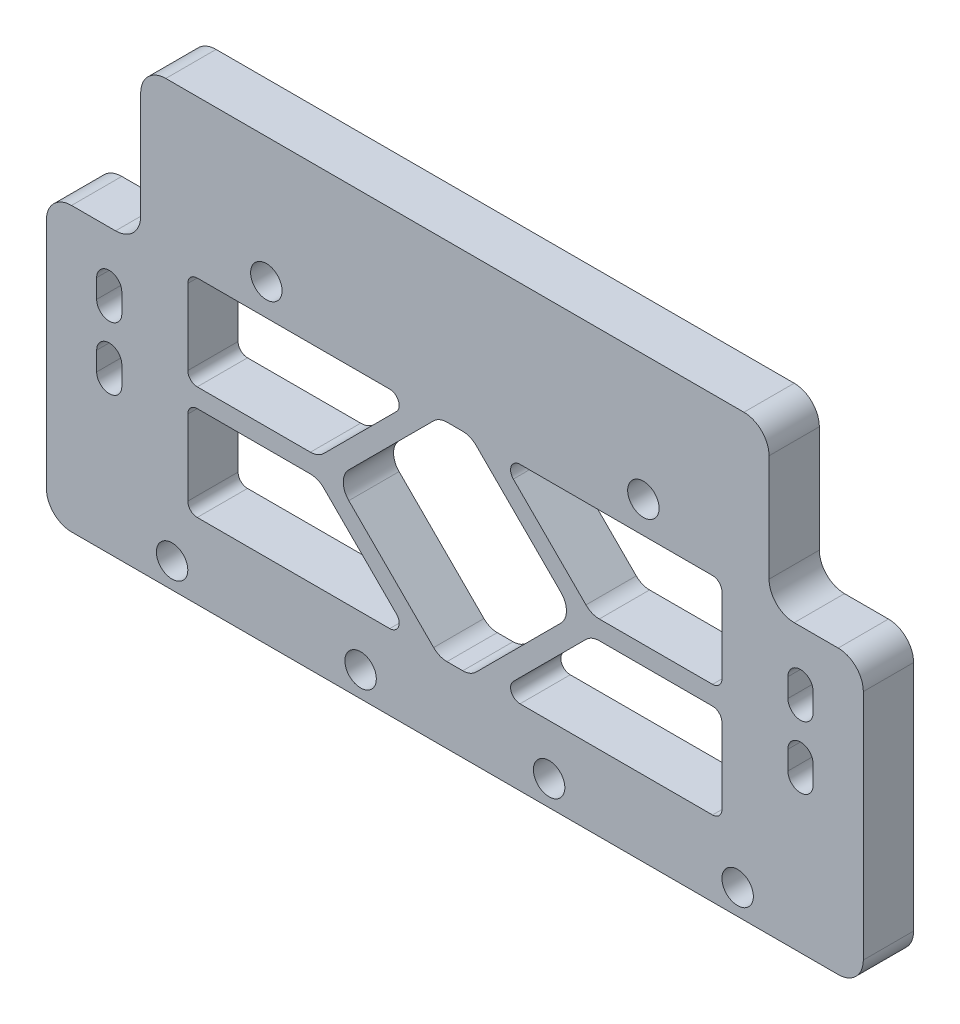
SolidWorks part; units mm, degrees
ref_plane "Plan de face" through (0, 0, 0) normal (0, 0, 1) x (1, 0, 0)
ref_plane "Plan de dessus" through (0, 0, 0) normal (0, 1, 0) x (1, 0, 0)
ref_plane "Plan de droite" through (0, 0, 0) normal (1, 0, 0) x (0, 0, -1)
sketch "Esquisse1" plane through (0, 0, 0) normal (0, 0, 1) x (1, 0, 0)
  line L1 (65, 4) -> (65, 41)
  line L2 (61, 45) -> (54, 45)
  line L3 (50, 49) -> (50, 66)
  line L4 (46, 70) -> (-46, 70)
  line L5 (0, 70) -> (0, 0) construction
  line L6 (-65, 4) -> (-65, 41)
  line L7 (-61, 45) -> (-54, 45)
  line L8 (-50, 49) -> (-50, 66)
  line L12 (-65, 0) -> (65, 0) construction
  line L13 (-61, 0) -> (61, 0)
  arc A0 (54, 45) -> (50, 49) centre (54, 49) cw
  arc A1 (61, 45) -> (65, 41) centre (61, 41) cw
  arc A2 (65, 4) -> (61, 0) centre (61, 4) cw
  arc A3 (-65, 4) -> (-61, 0) centre (-61, 4) ccw
  arc A4 (-54, 45) -> (-50, 49) centre (-54, 49) ccw
  arc A5 (-61, 45) -> (-65, 41) centre (-61, 41) ccw
  arc A6 (50, 66) -> (46, 70) centre (46, 66) ccw
  arc A7 (-46, 70) -> (-50, 66) centre (-46, 66) ccw
  point P13 (50, 45)
  point P16 (65, 45)
  point P25 (-50, 45)
  point P28 (-65, 45)
  point P31 (50, 70)
  point P34 (-50, 70)
  dimension "D5" = 4
  dimension "D1" = 65
  dimension "D2" = 15
  dimension "D3" = 45
  dimension "D4" = 25
  dimension "D7" = 130
extrude "Boss.-Extru.1" add sketch "Esquisse1" along normal blind 8
sketch "Esquisse2" plane through (0, 0, 8) normal (0, 0, 1) x (1, 0, 0)
  line L0 (65, 4) -> (65, 41) construction
  line L1 (-65, 0) -> (65, 0) construction
  line L2 (-65, 0) -> (-65, 10) construction
  line L3 (-65, 10) -> (65, 10) construction
  line L4 (65, 0) -> (65, 10) construction
  line L5 (-65, 5) -> (79.0692, 5) construction
  line L6 (0, 10) -> (0, -12.3812) construction
  line L7 (50, 49) -> (50, 66) construction
  line L8 (46, 70) -> (-46, 70) construction
  line L9 (0, 70) -> (0, 54.5793) construction
  circle A4 centre (30, 50) radius 2.5
  circle A5 centre (-30, 50) radius 2.5
  dimension "D7" = 5
  dimension "D1" = 10
  dimension "D5" = 20
  dimension "D6" = 20
extrude "Enlèv. mat.-Extru.1" cut sketch "Esquisse2" against normal through all
sketch "Esquisse4" plane through (0, 0, 8) normal (0, 0, 1) x (1, 0, 0)
  line L0 (0, 0) -> (0, 73.2883) construction
  line L9 (-42.5, 28.5) -> (73.4825, 28.5) construction
  line L14 (-41, 45) -> (-10.364, 45)
  line L15 (-42.5, 43.5) -> (-42.5, 31.5)
  line L16 (-41, 12) -> (-10.364, 12)
  line L17 (42.5, 43.5) -> (42.5, 31.5)
  line L18 (-9.3033, 42.4393) -> (-20.864, 30.8787)
  line L19 (-20.864, 26.1213) -> (-9.3033, 14.5607)
  line L20 (22.9853, 30) -> (41, 30)
  line L21 (22.9853, 27) -> (41, 27)
  line L22 (-3.3787, 44.1213) -> (-16.8787, 30.6213)
  line L23 (-16.8787, 26.3787) -> (-3.3787, 12.8787)
  line L24 (16.8787, 26.3787) -> (3.3787, 12.8787)
  line L25 (-42.5, 45) -> (-42.5, 30)
  line L26 (-4.6213, 42.8787) -> (-19, 28.5) construction
  line L27 (42.5, 45) -> (42.5, 30)
  line L28 (20.864, 26.1213) -> (9.3033, 14.5607)
  line L29 (3.3787, 44.1213) -> (16.8787, 30.6213)
  line L30 (-19, 28.5) -> (-4.6213, 14.1213) construction
  line L31 (-22.9853, 30) -> (-41, 30)
  line L32 (-22.9853, 27) -> (-41, 27)
  line L33 (9.3033, 42.4393) -> (20.864, 30.8787)
  line L34 (-61, 0) -> (61, 0) construction
  line L35 (-6.7426, 45) -> (-23.2426, 28.5) construction
  line L36 (-23.2426, 28.5) -> (-6.7426, 12) construction
  line L37 (-1.2574, 45) -> (1.2574, 45)
  line L38 (10.364, 45) -> (41, 45)
  line L39 (10.364, 12) -> (41, 12)
  line L40 (-1.2574, 12) -> (1.2574, 12)
  line L41 (-42.5, 25.5) -> (-42.5, 13.5)
  line L42 (-42.5, 27) -> (-42.5, 12)
  line L43 (42.5, 25.5) -> (42.5, 13.5)
  line L44 (42.5, 27) -> (42.5, 12)
  arc A0 (-22.9853, 27) -> (-20.864, 26.1213) centre (-22.9853, 24) cw
  arc A1 (-20.864, 30.8787) -> (-22.9853, 30) centre (-22.9853, 33) cw
  arc A2 (-16.8787, 30.6213) -> (-16.8787, 26.3787) centre (-14.7574, 28.5) ccw
  arc A3 (22.9853, 30) -> (20.864, 30.8787) centre (22.9853, 33) cw
  arc A4 (22.9853, 27) -> (20.864, 26.1213) centre (22.9853, 24) ccw
  arc A5 (-3.3787, 12.8787) -> (-1.2574, 12) centre (-1.2574, 15) ccw
  arc A6 (3.3787, 12.8787) -> (1.2574, 12) centre (1.2574, 15) cw
  arc A7 (16.8787, 26.3787) -> (16.8787, 30.6213) centre (14.7574, 28.5) ccw
  arc A8 (3.3787, 44.1213) -> (1.2574, 45) centre (1.2574, 42) ccw
  arc A9 (-3.3787, 44.1213) -> (-1.2574, 45) centre (-1.2574, 42) cw
  arc A10 (9.3033, 14.5607) -> (10.364, 12) centre (10.364, 13.5) ccw
  arc A11 (-9.3033, 14.5607) -> (-10.364, 12) centre (-10.364, 13.5) cw
  arc A12 (-9.3033, 42.4393) -> (-10.364, 45) centre (-10.364, 43.5) ccw
  arc A13 (9.3033, 42.4393) -> (10.364, 45) centre (10.364, 43.5) cw
  arc A14 (41, 45) -> (42.5, 43.5) centre (41, 43.5) cw
  arc A15 (41, 12) -> (42.5, 13.5) centre (41, 13.5) ccw
  arc A16 (-42.5, 13.5) -> (-41, 12) centre (-41, 13.5) ccw
  arc A17 (-41, 45) -> (-42.5, 43.5) centre (-41, 43.5) ccw
  arc A18 (-41, 27) -> (-42.5, 25.5) centre (-41, 25.5) ccw
  arc A19 (-41, 30) -> (-42.5, 31.5) centre (-41, 31.5) cw
  arc A20 (41, 27) -> (42.5, 25.5) centre (41, 25.5) cw
  arc A21 (41, 30) -> (42.5, 31.5) centre (41, 31.5) ccw
  point P13 (23.1768, 33.4429)
  point P14 (-2.1727, 13.8902)
  point P15 (-22.9939, 30)
  point P16 (0, 53.1432)
  point P38 (-21.7426, 27)
  point P41 (-21.7426, 30)
  point P47 (21.7426, 30)
  point P50 (21.7426, 27)
  point P53 (-2.5, 12)
  point P56 (2.5, 12)
  point P61 (2.5, 45)
  point P64 (-2.5, 45)
  point P67 (6.7426, 12)
  dimension "D7" = 3
  dimension "D8" = 3
  dimension "D9" = 1.5
  dimension "D10" = 1.5
  dimension "D2" = 5
  dimension "D3" = 33
  dimension "D4" = 3
  dimension "D5" = 85
  dimension "D6" = 12
  dimension "D1" = 3
extrude "Enlèv. mat.-Extru.4" cut sketch "Esquisse4" against normal through all contours L31 L18 L14 L15 | L19 L32 L15 L16 | L29 L14 L22 L23 L16 L24 | L14 L33 L20 L17 | L21 L28 L16 L17
sketch "Esquisse5" plane through (0, 0, 8) normal (0, 0, 1) x (1, 0, 0)
  circle A0 centre (-45, 4) radius 2.5 construction
  circle A1 centre (-15, 4) radius 2.5 construction
  circle A2 centre (15, 4) radius 2.5 construction
  circle A3 centre (45, 4) radius 2.5 construction
  circle A4 centre (-45, 4) radius 2.5
  circle A5 centre (-15, 4) radius 2.5
  circle A6 centre (15, 4) radius 2.5
  circle A7 centre (45, 4) radius 2.5
extrude "Enlèv. mat.-Extru.5" cut sketch "Esquisse5" against normal through all
sketch "Esquisse6" plane through (0, 0, 8) normal (0, 0, 1) x (1, 0, 0)
  line L0 (55, 27.0535) -> (55, 24.0535) construction
  line L1 (57, 27.0535) -> (57, 24.0535)
  line L2 (53, 27.0535) -> (53, 24.0535)
  line L3 (55, 25.5535) -> (55, 35.5535) construction
  line L4 (55, 30.5535) -> (70.948, 30.5535) construction
  line L5 (55, 34.0535) -> (55, 37.0535) construction
  line L6 (57, 34.0535) -> (57, 37.0535)
  line L7 (53, 34.0535) -> (53, 37.0535)
  line L8 (0, 0) -> (0, -12.8208) construction
  line L9 (-61, 0) -> (61, 0) construction
  line L10 (-55, 25.5535) -> (-55, 35.5535) construction
  line L11 (-55, 34.0535) -> (-55, 37.0535) construction
  line L12 (-57, 34.0535) -> (-57, 37.0535)
  line L13 (-53, 34.0535) -> (-53, 37.0535)
  line L14 (-55, 27.0535) -> (-55, 24.0535) construction
  line L15 (-57, 27.0535) -> (-57, 24.0535)
  line L16 (-53, 27.0535) -> (-53, 24.0535)
  circle A0 centre (55, 25.5535) radius 1.5 construction
  circle A1 centre (55, 35.5535) radius 1.5 construction
  circle A2 centre (55, 25.5535) radius 1.5 construction
  circle A3 centre (55, 35.5535) radius 1.5 construction
  arc A4 (57, 27.0535) -> (53, 27.0535) centre (55, 27.0535) ccw
  arc A5 (53, 24.0535) -> (57, 24.0535) centre (55, 24.0535) ccw
  arc A6 (57, 34.0535) -> (53, 34.0535) centre (55, 34.0535) cw
  arc A7 (53, 37.0535) -> (57, 37.0535) centre (55, 37.0535) cw
  circle A8 centre (55, 35.5535) radius 1.5 construction
  circle A9 centre (-55, 35.5535) radius 1.5 construction
  circle A10 centre (-55, 35.5535) radius 1.5 construction
  circle A11 centre (-55, 25.5535) radius 1.5 construction
  arc A12 (-57, 34.0535) -> (-53, 34.0535) centre (-55, 34.0535) ccw
  arc A13 (-53, 37.0535) -> (-57, 37.0535) centre (-55, 37.0535) ccw
  arc A14 (-57, 27.0535) -> (-53, 27.0535) centre (-55, 27.0535) cw
  arc A15 (-53, 24.0535) -> (-57, 24.0535) centre (-55, 24.0535) cw
  point P8 (55, 25.5535)
  point P17 (55, 35.5535)
  point P34 (-55, 35.5535)
  point P41 (-55, 25.5535)
  dimension "D1" = 2
  dimension "D2" = 3
extrude "Enlèv. mat.-Extru.6" cut sketch "Esquisse6" against normal through all
